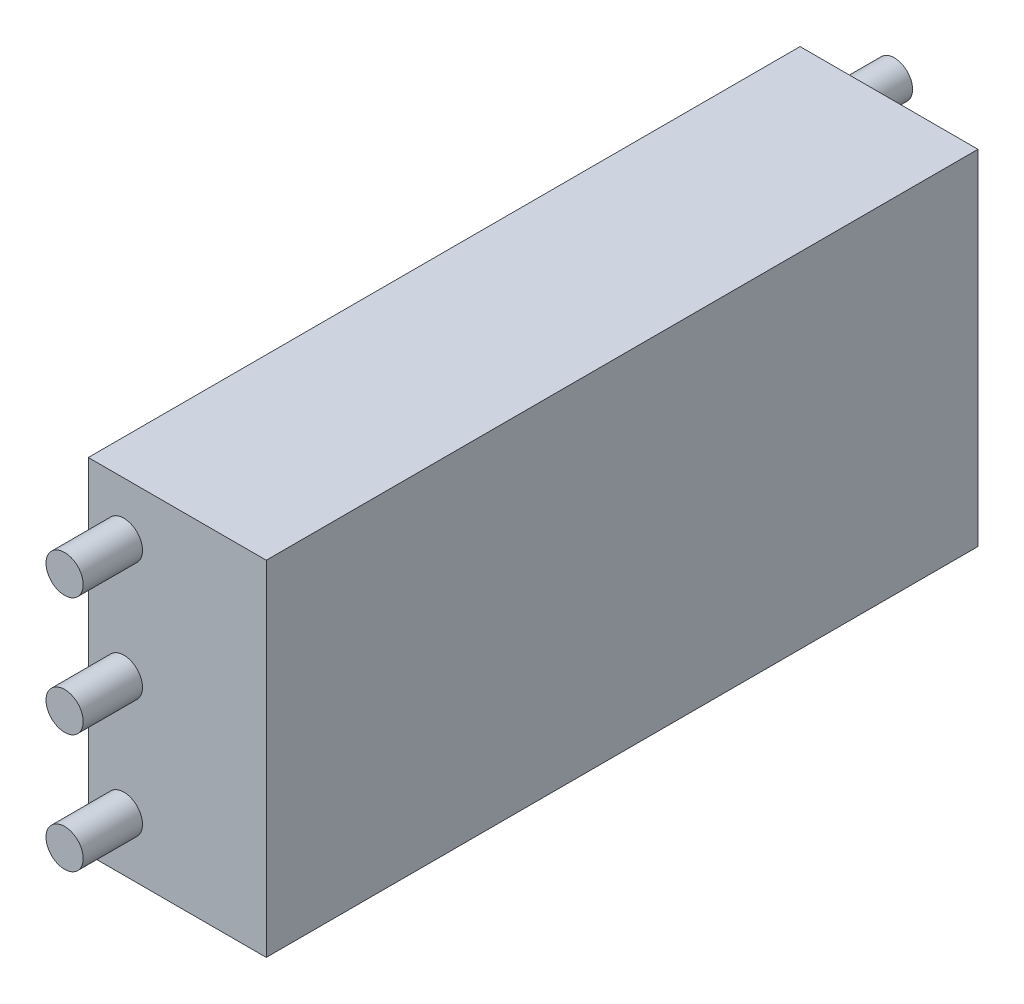
SolidWorks part; units mm, degrees
ref_plane "Front" through (0, 0, 0) normal (0, 0, 1) x (1, 0, 0)
ref_plane "Top" through (0, 0, 0) normal (0, 1, 0) x (1, 0, 0)
ref_plane "Right" through (0, 0, 0) normal (1, 0, 0) x (0, 0, -1)
sketch "Sketch1" plane through (0, 0, 0) normal (1, 0, 0) x (0, 0, -1)
  line L1 (0, 0) -> (60, 0)
  line L2 (0, 0) -> (0, 29)
  line L3 (0, 29) -> (60, 29)
  line L4 (60, 0) -> (60, 29)
  dimension "D1" = 29
  dimension "D2" = 60
extrude "Boss-Extrude1" add sketch "Sketch1" along normal blind 15
sketch "Sketch2" plane through (0, 0, 0) normal (0, 0, 1) x (1, 0, 0)
  line L0 (3, 24.5) -> (3, 4.5) construction
  line L1 (0, 29) -> (0, 0) construction
  circle A0 centre (3, 24.5) radius 1.5674
  circle A1 centre (3, 14.5) radius 1.5674
  circle A2 centre (3, 4.5) radius 1.5674
  point P2 (3, 14.5)
  point P11 (0, 14.5)
  dimension "D1" = 20
  dimension "D2" = 3
extrude "Boss-Extrude2" add sketch "Sketch2" along normal blind 5
sketch "Sketch3" plane through (0, 0, -60) normal (0, 0, -1) x (-1, 0, 0)
  circle A0 centre (-2.9474, 25.6152) radius 1.5394
  circle A1 centre (-2.9474, 3.4192) radius 1.5394
extrude "Boss-Extrude3" add sketch "Sketch3" along normal blind 5
